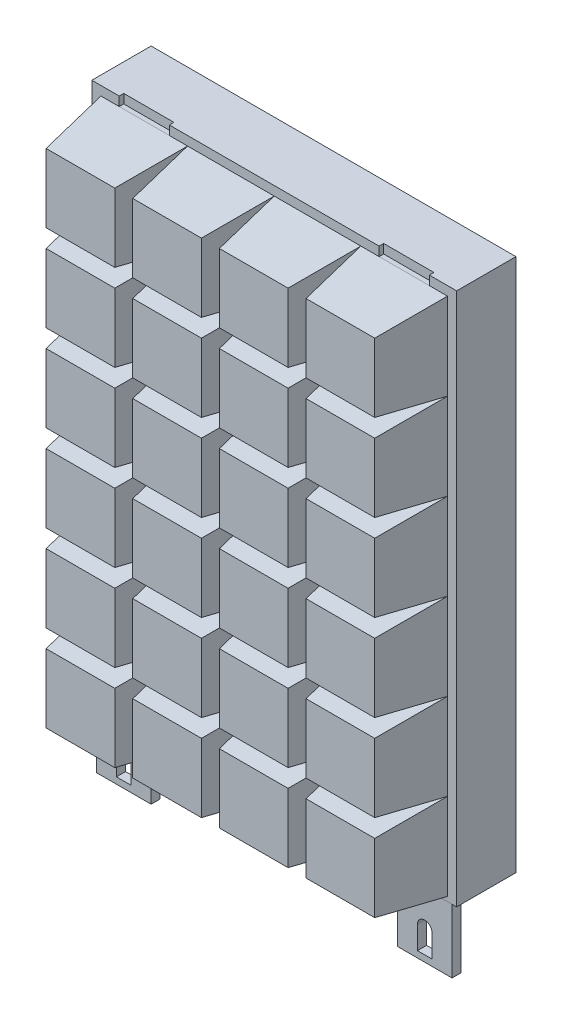
SolidWorks part; units mm, degrees
material "ABS"
ref_plane "TOP" through (0, 0, 0) normal (0, 0, 1) x (1, 0, 0)
ref_plane "FRONT" through (0, 0, 0) normal (0, 1, 0) x (1, 0, 0)
ref_plane "RIGHT" through (0, 0, 0) normal (1, 0, 0) x (0, 0, -1)
sketch "Эскиз1" plane through (0, 0, 0) normal (0, 0, 1) x (1, 0, 0)
  line L0 (-40, 58.5) -> (40, -58.5) construction
  line L1 (-40, 58.5) -> (40, 58.5)
  line L2 (-40, 58.5) -> (-40, -58.5)
  line L3 (-40, -58.5) -> (40, -58.5)
  line L4 (40, 58.5) -> (40, -58.5)
  point P4 (0, 0)
  dimension "D1" = 117
  dimension "D2" = 80
extrude "Бобышка-Вытянуть1" add sketch "Эскиз1" along normal blind 13
sketch "Эскиз2" plane through (0, 0, 13) normal (0, 0, 1) x (1, 0, 0)
  line L1 (-38, 56.5) -> (-19, 56.5)
  line L2 (-38, 56.5) -> (-38, 37.5)
  line L3 (-38, 37.5) -> (-19, 37.5)
  line L4 (-19, 56.5) -> (-19, 37.5)
  line L12 (-38, 56.5) -> (-38, -56.5)
  line L13 (-38, -56.5) -> (38, -56.5)
  line L14 (38, -56.5) -> (38, 56.5)
  line L15 (38, 56.5) -> (-38, 56.5)
  line L16 (-38, 56.5) -> (-38, -56.5) construction
  line L17 (-38, -56.5) -> (38, -56.5) construction
  line L18 (38, -56.5) -> (38, 56.5) construction
  line L19 (38, 56.5) -> (-38, 56.5) construction
  point P4 (-36.9628, 56.5)
  dimension "D1" = 19
  dimension "D2" = 2
extrude "Бобышка-Вытянуть2" add sketch "Эскиз2" along normal blind 14 draft 8
pattern_linear "Линейный массив1" count 4 spacing 19 along (1, 0, 0) count 6 spacing 19 along (0, -1, 0) of "Бобышка-Вытянуть2"
sketch "Эскиз4" plane through (0, 0, 13) normal (0, 0, 1) x (1, 0, 0)
  line L0 (-40, -58.5) -> (40, -58.5) construction
  line L1 (-39, -58.5) -> (-27, -58.5)
  line L2 (-39, -58.5) -> (-39, -72.5)
  line L3 (-39, -72.5) -> (-27, -72.5)
  line L4 (-27, -58.5) -> (-27, -72.5)
  line L5 (0, -58.5) -> (0, -75.6828) construction
  line L10 (-33, -58.5) -> (-33, -72.5) construction
  line L11 (34.3352, -64.5) -> (31.1352, -64.5) construction
  line L12 (-34.3352, -64.5) -> (-31.1352, -64.5) construction
  line L13 (-34.6, -66.1) -> (-34.6, -71.1)
  line L14 (-34.6, -71.1) -> (-31.4, -71.1)
  line L15 (-31.4, -66.1) -> (-31.4, -71.1)
  line L16 (33, -58.5) -> (33, -72.5) construction
  line L17 (31.4, -66.1) -> (31.4, -71.1)
  line L18 (34.6, -71.1) -> (31.4, -71.1)
  line L19 (34.6, -66.1) -> (34.6, -71.1)
  line L20 (27, -58.5) -> (27, -72.5)
  line L21 (39, -72.5) -> (27, -72.5)
  line L22 (39, -58.5) -> (39, -72.5)
  line L23 (39, -58.5) -> (27, -58.5)
  arc A0 (-31.4, -66.1) -> (-34.6, -66.1) centre (-33, -66.1) ccw
  arc A1 (31.4, -66.1) -> (34.6, -66.1) centre (33, -66.1) cw
  point P18 (-31.2719, -66.1)
  dimension "D1" = 14
  dimension "D2" = 12
  dimension "D3" = 3.2
  dimension "D4" = 1.4
  dimension "D5" = 8
  dimension "D6" = 54
extrude "Бобышка-Вытянуть3" add sketch "Эскиз4" against normal blind 2 separate body
sketch "Эскиз3" plane through (0, 0, 13) normal (0, 0, 1) x (1, 0, 0)
  line L0 (0, 58.5) -> (0, 75.7077) construction
  line L1 (40, 58.5) -> (-40, 58.5) construction
  line L2 (-19, 56.5) -> (-38, 56.5) construction
  line L3 (-34, 58.5) -> (-23, 58.5)
  line L4 (-34, 58.5) -> (-34, 56.5)
  line L5 (-34, 56.5) -> (-23, 56.5)
  line L6 (-23, 58.5) -> (-23, 56.5)
  line L7 (23, 58.5) -> (23, 56.5)
  line L8 (34, 56.5) -> (23, 56.5)
  line L9 (34, 58.5) -> (34, 56.5)
  line L10 (34, 58.5) -> (23, 58.5)
  dimension "D1" = 11
  dimension "D2" = 46
extrude "Вырез-Вытянуть1" cut sketch "Эскиз3" against normal blind 1
equation "\"D3@Линейный массив1\"=\"D1@Эскиз2\""
equation "\"D4@Линейный массив1\"=\"D1@Эскиз2\""
